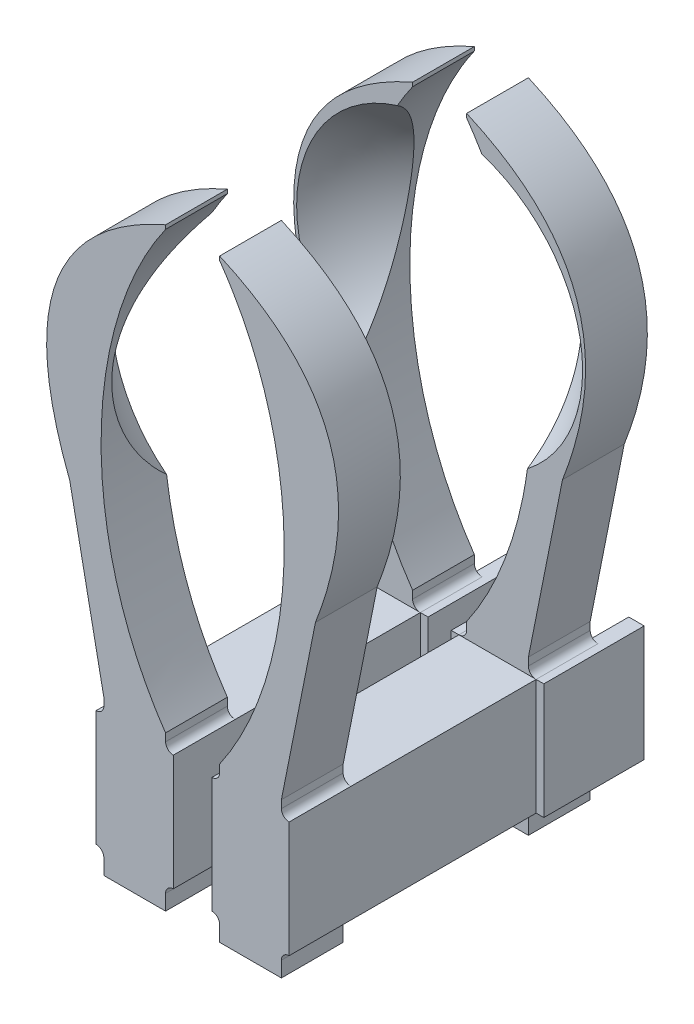
SolidWorks part; units mm, degrees
ref_plane "前视基准面" through (0, 0, 0) normal (0, 0, 1) x (1, 0, 0)
ref_plane "上视基准面" through (0, 0, 0) normal (0, 1, 0) x (1, 0, 0)
ref_plane "右视基准面" through (0, 0, 0) normal (1, 0, 0) x (0, 0, -1)
sketch "草图1" plane through (0, 0, 0) normal (0, 0, 1) x (1, 0, 0)
  line L0 (-8, 0) -> (-8, 20)
  line L1 (0, 0) -> (-8, 0)
  line L2 (0, 0) -> (0, 20)
  line L5 (-1008, 0) -> (48992, 0) construction
  line L6 (-8, -980) -> (-8, 77) construction
  line L11 (-8, 77) -> (-8, 76.4918)
  line L13 (0, 20) -> (0, 0)
  line L14 (-11.5, -1000) -> (-11.5, 49000) construction
  line L15 (0, 20) -> (4.4136, 42.1031)
  line L16 (-15, 77) -> (-15, 76.4918)
  line L17 (-23, 0) -> (-15, 0)
  line L18 (-15, 0) -> (-15, 20)
  line L19 (-23, 0) -> (-23, 20)
  line L20 (-23, 20) -> (-27.4136, 42.1031)
  circle A0 centre (-4, 10) radius 2.3
  circle A1 centre (-19, 10) radius 2.3
  spline S0 degree 3 poles (-8, 20) (2.9977, 35.8714) (3.2889, 60.4536) (-8, 76.4918) knots 0 0 0 0 0.972662 0.972662 0.972662 0.972662
  spline S1 degree 2 poles (-8, 77) (14.1984, 67.2608) (4.4136, 42.1031) knots 0 0 0 1 1 1
  spline S2 degree 2 poles (-15, 77) (-37.1984, 67.2608) (-27.4136, 42.1031) knots 0 0 0 1 1 1
  spline S3 degree 3 poles (-15, 20) (-25.9977, 35.8714) (-26.2889, 60.4536) (-15, 76.4918) knots 0 0 0 0 0.972662 0.972662 0.972662 0.972662
  point P2 (-11.5, 0)
  point P11 (-8, 10)
  point P12 (0, 20)
  point P27 (-15, 10)
  dimension "D4" = 10
  dimension "D1" = 3.5
  dimension "D2" = 20
  dimension "D5" = 4
extrude "凸台-拉伸1" add sketch "草图1" along normal blind 8 contours S1 L11 S0 L0 L1 L2 L15 A0 | L16 S3 L18 L17 L19 L20 S2 | A1
sketch "草图2" plane through (0, 0, 0) normal (1, 0, 0) x (0, 0, -1)
  line L0 (-8, 0) -> (-8, 20) construction
  line L1 (-8, 18) -> (0, 18)
  line L2 (-8, 18) -> (-8, 3)
  line L3 (-8, 3) -> (0, 3)
  line L4 (0, 18) -> (0, 3)
  line L5 (0, 0) -> (0, 20) construction
  line L6 (-8, 0) -> (0, 0) construction
  dimension "D1" = 15
  dimension "D2" = 3
extrude "凸台-拉伸2" add sketch "草图2" along normal blind 2
sketch "草图3" plane through (0, 0, 0) normal (0, 0, -1) x (-1, 0, 0)
  line L1 (-2, 18) -> (0, 18)
  line L2 (-2, 18) -> (-2, 3)
  line L3 (-2, 3) -> (0, 3)
  line L4 (0, 18) -> (0, 3)
extrude "凸台-拉伸3" add sketch "草图3" along normal blind 5
sketch "草图4" plane through (-8, 0, 0) normal (-1, 0, 0) x (0, 0, 1)
  line L1 (0, 18) -> (8, 18)
  line L2 (0, 18) -> (0, 3)
  line L3 (0, 3) -> (8, 3)
  line L4 (8, 18) -> (8, 3)
extrude "凸台-拉伸4" add sketch "草图4" along normal blind 2
sketch "草图5" plane through (0, 0, 0) normal (0, 0, -1) x (-1, 0, 0)
  line L1 (8, 18) -> (10, 18)
  line L2 (8, 18) -> (8, 3)
  line L3 (8, 3) -> (10, 3)
  line L4 (10, 18) -> (10, 3)
extrude "凸台-拉伸5" add sketch "草图5" along normal blind 5
fillet "圆角1" radius 1 4 edges at (0, 3, 4) (-8, 3, 4) (0, 18, 4) (-8, 18, 4)
sketch "草图7" plane through (-15, 0, 0) normal (1, 0, 0) x (0, 0, -1)
  line L0 (-8, 0) -> (-8, 20) construction
  line L1 (-8, 18) -> (0, 18)
  line L2 (-8, 18) -> (-8, 3)
  line L3 (-8, 3) -> (0, 3)
  line L4 (0, 18) -> (0, 3)
  line L5 (0, 0) -> (0, 20) construction
  line L6 (-8, 0) -> (0, 0) construction
  dimension "D1" = 15
  dimension "D2" = 3
extrude "凸台-拉伸6" add sketch "草图7" along normal blind 2
sketch "草图8" plane through (-23, 0, 0) normal (-1, 0, 0) x (0, 0, 1)
  line L0 (0, 0) -> (0, 20) construction
  line L1 (0, 18) -> (8, 18)
  line L2 (0, 18) -> (0, 3)
  line L3 (0, 3) -> (8, 3)
  line L4 (8, 18) -> (8, 3)
  line L5 (8, 18) -> (-5, 18) construction
  line L6 (8, 0) -> (8, 20) construction
  dimension "D1" = 15
extrude "凸台-拉伸7" add sketch "草图8" along normal blind 2
sketch "草图9" plane through (0, 0, 0) normal (0, 0, -1) x (-1, 0, 0)
  line L1 (13, 18) -> (15, 18)
  line L2 (13, 18) -> (13, 3)
  line L3 (13, 3) -> (15, 3)
  line L4 (15, 18) -> (15, 3)
  line L5 (25, 18) -> (23, 18)
  line L6 (25, 18) -> (25, 3)
  line L7 (25, 3) -> (23, 3)
  line L8 (23, 18) -> (23, 3)
extrude "凸台-拉伸8" add sketch "草图9" along normal blind 5
fillet "圆角2" radius 1 4 edges at (-15, 18, 4) (-23, 18, 4) (-23, 3, 4) (-15, 3, 4)
sketch "草图11" plane through (0, 0, 8) normal (0, 0, 1) x (1, 0, 0)
  line L0 (-1015, 0) -> (48985, 0) construction
  line L1 (-11.5, -1000) -> (-11.5, 49000) construction
  line L2 (-1011.5, 55.6905) -> (48988.5, 55.6905) construction
  circle A0 centre (-11.5, 55.6905) radius 16 construction
  dimension "D2" = 32
  dimension "D1" = 3.5
ref_plane "基准面6" through (-11.5, 55.6905, 8) normal (0, 1, 0) x (1, 0, 0)
sketch "草图14" plane through (-11.5, 55.6905, 8) normal (0, 1, 0) x (1, 0, 0)
  line L0 (0, -1000) -> (0, 49000) construction
  line L1 (-5.2, 8) -> (-9.8, 8) construction
  point P4 (0, -12)
  point P7 (0, 8)
  point P10 (0, -32)
  dimension "D1" = 40
  dimension "D2" = 20
sketch "草图15" plane through (0, 0, 8) normal (0, 0, 1) x (1, 0, 0)
  line L0 (-1011.5, 55.6905) -> (48988.5, 55.6905) construction
ref_plane "基准面9" through (0, 0, 40) normal (0, 0, -1) x (-1, 0, 0)
sketch "草图18" plane through (0, 0, 40) normal (0, 0, -1) x (-1, 0, 0)
  line L2 (8, 19) -> (8, 20) construction
  line L3 (8, 76.4918) -> (8, 77) construction
  line L4 (-4.4136, 42.1031) -> (0, 20) construction
  line L5 (0, 20) -> (0, 19) construction
  line L9 (0, 2) -> (0, 0) construction
  line L10 (0, 0) -> (8, 0) construction
  line L11 (8, 0) -> (8, 2) construction
  line L13 (23, 0) -> (23, 2) construction
  line L17 (23, 19) -> (23, 20) construction
  line L18 (23, 20) -> (27.4136, 42.1031) construction
  line L19 (15, 77) -> (15, 76.4918) construction
  line L20 (15, 20) -> (15, 19) construction
  line L24 (15, 2) -> (15, 0) construction
  line L25 (15, 0) -> (23, 0) construction
  line L28 (8, 19) -> (8, 20)
  line L29 (8, 76.4918) -> (8, 77)
  line L30 (-4.4136, 42.1031) -> (0, 20)
  line L31 (0, 20) -> (0, 19)
  line L35 (0, 2) -> (0, 0)
  line L36 (0, 0) -> (8, 0)
  line L37 (8, 0) -> (8, 2)
  line L39 (23, 0) -> (23, 2)
  line L43 (23, 19) -> (23, 20)
  line L44 (23, 20) -> (27.4136, 42.1031)
  line L45 (15, 77) -> (15, 76.4918)
  line L46 (15, 20) -> (15, 19)
  line L50 (15, 2) -> (15, 0)
  line L51 (15, 0) -> (23, 0)
  line L52 (-1, 18) -> (-1, 3)
  line L53 (24, 18) -> (24, 3)
  line L54 (14, 18) -> (14, 3)
  line L55 (9, 18) -> (9, 3)
  arc A0 (8, 19) -> (9, 18) centre (9, 19) ccw construction
  arc A1 (-1, 18) -> (0, 19) centre (-1, 19) ccw construction
  arc A2 (0, 2) -> (-1, 3) centre (-1, 2) ccw construction
  arc A3 (9, 3) -> (8, 2) centre (9, 2) ccw construction
  arc A4 (24, 3) -> (23, 2) centre (24, 2) ccw construction
  arc A5 (23, 19) -> (24, 18) centre (24, 19) ccw construction
  arc A6 (14, 18) -> (15, 19) centre (14, 19) ccw construction
  arc A7 (15, 2) -> (14, 3) centre (14, 2) ccw construction
  arc A8 (8, 19) -> (9, 18) centre (9, 19) ccw
  arc A9 (-1, 18) -> (0, 19) centre (-1, 19) ccw
  arc A10 (0, 2) -> (-1, 3) centre (-1, 2) ccw
  arc A11 (9, 3) -> (8, 2) centre (9, 2) ccw
  arc A12 (24, 3) -> (23, 2) centre (24, 2) ccw
  arc A13 (23, 19) -> (24, 18) centre (24, 19) ccw
  arc A14 (14, 18) -> (15, 19) centre (14, 19) ccw
  arc A15 (15, 2) -> (14, 3) centre (14, 2) ccw
  parabola Q0 (8, 77) -> (-4.4136, 42.1031) focus (3.1931, 61.1634) apex (-5.4082, 65.3099) construction
  parabola Q1 (27.4136, 42.1031) -> (15, 77) focus (19.8069, 61.1634) apex (28.4082, 65.3099) construction
  parabola Q2 (8, 77) -> (-4.4136, 42.1031) focus (3.1931, 61.1634) apex (-5.4082, 65.3099)
  parabola Q3 (27.4136, 42.1031) -> (15, 77) focus (19.8069, 61.1634) apex (28.4082, 65.3099)
  spline S0 degree 3 poles (719.8773, 1873.3548) (-162.7516, -2151.5456) (-381.0051, 2214.8786) (908.8263, -1692.4868) knots -4.350132 -4.350132 -4.350132 -4.350132 5.264387 5.264387 5.264387 5.264387 only from (8, 20) to (8, 76.4918) construction
  spline S1 degree 3 poles (-885.8361, -1692.5164) (404.0022, 2214.8885) (185.7552, -2151.5287) (-696.8691, 1873.3174) knots -4.291749 -4.291749 -4.291749 -4.291749 5.322765 5.322765 5.322765 5.322765 only from (15, 76.4918) to (15, 20) construction
  spline S2 degree 3 poles (8, 20) (-2.9977, 35.8714) (-3.2889, 60.4536) (8, 76.4918) knots 0 0 0 0 0.972662 0.972662 0.972662 0.972662
  spline S3 degree 3 poles (15, 76.4918) (26.2889, 60.4536) (25.9977, 35.8714) (15, 20) knots 0 0 0 0 0.972662 0.972662 0.972662 0.972662
extrude "凸台-拉伸10" add sketch "草图18" along normal blind 8 separate body
sketch "草图13" plane through (-11.5, 55.6905, 8) normal (0, 1, 0) x (1, 0, 0)
  line L0 (0, -1000) -> (0, 49000) construction
  line L1 (0, -33.4329) -> (0, 10.2635)
  line L2 (3.5, 0) -> (11.8578, 0) construction
  line L3 (0, -33.4329) -> (0, -34.27)
  arc A0 (0, 10.2635) -> (-21.8451, -11.9554) centre (0, -11.5847) ccw
  arc A1 (-21.8451, -11.9554) -> (0, -34.27) centre (0, -12.42) ccw
  point P4 (0, -23.1647)
  point P5 (0, -24)
  point P8 (0, -12)
  point P11 (0, -12.42)
  point P13 (0, 0)
  dimension "D1" = 11.58
  dimension "D2" = 24
  dimension "D3" = 12
  dimension "D4" = 0.42
revolve "切除-旋转1" cut sketch "草图13" angle 360 about L0
sketch "草图22" plane through (0, 0, 32) normal (0, 0, -1) x (-1, 0, 0)
  line L0 (14, 18) -> (14, 3) construction
  line L1 (14, 18) -> (24, 18)
  line L2 (14, 18) -> (14, 3)
  line L3 (14, 3) -> (24, 3)
  line L4 (24, 18) -> (24, 3)
  line L6 (-1, 18) -> (9, 18)
  line L7 (-1, 18) -> (-1, 3)
  line L8 (-1, 3) -> (9, 3)
  line L9 (9, 18) -> (9, 3)
  arc A0 (14, 18) -> (15, 19) centre (14, 19) ccw construction
extrude "凸台-拉伸12" add sketch "草图22" along normal up to surface (24 mm away) up to face at (-19.1388, 23.0092, 8)
